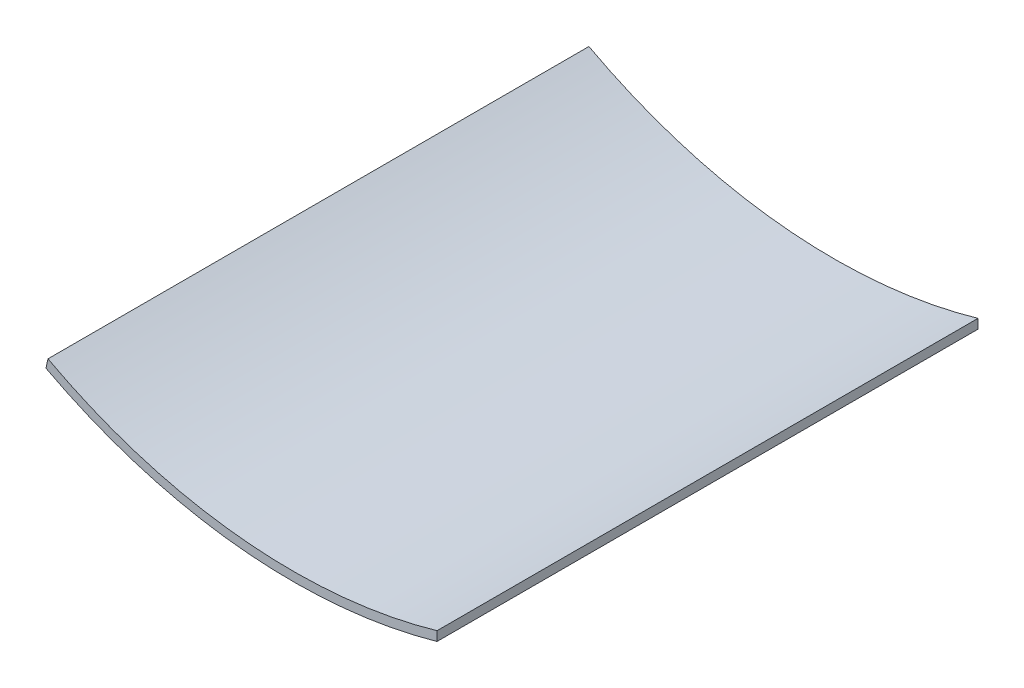
SolidWorks part; units mm, degrees
ref_plane "Front Plane" through (0, 0, 0) normal (1, 0, 0) x (0, 1, 0)
ref_plane "Top Plane" through (0, 0, 0) normal (0, 0, 1) x (0, 1, 0)
ref_plane "Right Plane" through (0, 0, 0) normal (0, 1, 0) x (-1, 0, 0)
sketch "Sketch1" plane through (0, 0, 0) normal (0, 0, 1) x (0, 1, 0)
  line L0 (0, -50.8) -> (-178.9855, -50.8) construction
  line L1 (0, 0) -> (10.5619, 49.6899) construction
  line L2 (0, 0) -> (-175.0743, 37.2132) construction
  line L3 (10.5619, 49.6899) -> (-164.5124, 86.9031) construction
  line L4 (-175.0743, 37.2132) -> (-164.5124, 86.9031) construction
  line L5 (-164.5124, 86.9031) -> (-161.2818, 86.2164)
  line L6 (-178.9855, -50.8) -> (-175.6828, -50.8)
  circle A0 centre (0, 0) radius 50.8 construction
  circle A1 centre (0, 0) radius 182.88 construction
  circle A2 centre (0, 0) radius 186.055 construction
  arc A3 (-161.2818, 86.2164) -> (-175.6828, -50.8) centre (0, 0) ccw
  arc A4 (-164.5124, 86.9031) -> (-178.9855, -50.8) centre (0, 0) ccw
  dimension "D1" = 101.6
  dimension "D2" = 132.08
  dimension "D3" = 3.175
  dimension "D4" = 12
extrude "Boss-Extrude1" add sketch "Sketch1" along normal blind 190.5
